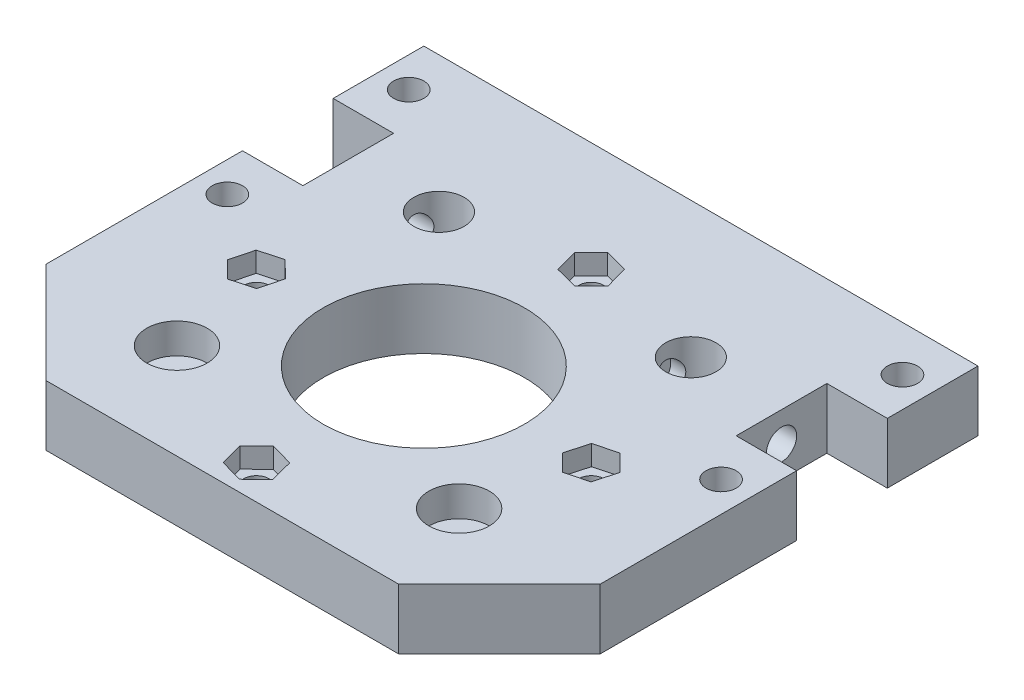
SolidWorks part; units mm, degrees
material "HDPE-green"
ref_plane "Front Plane" through (0, 0, 0) normal (0, 0, 1) x (1, 0, 0)
ref_plane "Top Plane" through (0, 0, 0) normal (0, 1, 0) x (1, 0, 0)
ref_plane "Right Plane" through (0, 0, 0) normal (1, 0, 0) x (0, 0, -1)
sketch "Sketch1" plane through (0, 0, 0) normal (0, 1, 0) x (1, 0, 0)
  line L1 (-33, 25) -> (33, 25)
  line L2 (-33, 25) -> (-33, -70)
  line L3 (-33, -70) -> (33, -70)
  line L4 (33, 25) -> (33, -70)
  circle A0 centre (0, -30) radius 20
  dimension "D6" = 40
  dimension "D1" = 66
  dimension "D2" = 33
  dimension "D3" = 25
  dimension "D4" = 70
  dimension "D5" = 30
extrude "Boss-Extrude1" add sketch "Sketch1" along normal blind 12
sketch "Sketch3" plane through (0, 12, 0) normal (0, 1, 0) x (1, 0, 0)
  line L1 (55, 7) -> (43, 7)
  line L2 (33, 25) -> (33, -70)
  line L3 (43, 7) -> (43, -11)
  line L4 (43, -11) -> (55, -11)
  line L6 (33, -70) -> (55, -70)
  line L7 (55, -70) -> (55, -11)
  line L8 (33, 25) -> (55, 25)
  line L9 (55, 7) -> (55, 25)
  dimension "D1" = 12
  dimension "D2" = 18
  dimension "D3" = 18
  dimension "D4" = 22
extrude "Boss-Extrude3" add sketch "Sketch3" against normal blind 12
mirror "Mirror1" about plane through (0, 0, 0) normal (1, 0, 0) of "Boss-Extrude3"
sketch "Sketch6" plane through (0, 12, 0) normal (0, 1, 0) x (1, 0, 0)
  line L0 (-63.5336, -51) -> (64.8117, -51) construction
  circle A1 centre (-28, -51) radius 6
  circle A2 centre (28, -51) radius 6
  circle A3 centre (0, -30) radius 20 construction
  dimension "D2" = 28
  dimension "D3" = 28
  dimension "D4" = 12
  dimension "D5" = 12
  dimension "D1" = 21
extrude "Cut-Extrude2" cut sketch "Sketch6" against normal blind 6
chamfer "Chamfer1" distance 20 angle 45 2 edges at (55, 6, 70) (-55, 6, 70)
sketch "Sketch7" plane through (0, 12, 0) normal (0, 1, 0) x (1, 0, 0)
  line L0 (-49, 22.071) -> (-49, -31.0852) construction
  line L1 (-59.9918, 16) -> (-35.4854, 16) construction
  line L2 (-63.8876, -20) -> (-39.0752, -20) construction
  line L3 (-55, -11) -> (-43, -11) construction
  line L4 (-42.1899, -2) -> (-20.2042, -2) construction
  line L6 (-43, -11) -> (-43, 7) construction
  circle A0 centre (-49, 16) radius 3
  circle A1 centre (-49, -20) radius 3
  circle A2 centre (-25, -2) radius 5
  dimension "D2" = 6
  dimension "D3" = 6
  dimension "D4" = 18
  dimension "D5" = 10
  dimension "D1" = 9
extrude "Cut-Extrude3" cut sketch "Sketch7" against normal up to next
sketch "Sketch9" plane through (-43, 0, 0) normal (-1, 0, 0) x (0, 0, 1)
  line L0 (11, 12) -> (-7, 12) construction
  line L1 (-7, 0) -> (-7, 12) construction
  circle A0 centre (2, 6) radius 3
  dimension "D1" = 6
  dimension "D2" = 6
  dimension "D3" = 9
extrude "Cut-Extrude5" cut sketch "Sketch9" against normal blind 25
mirror "Mirror2" about plane through (0, 0, 0) normal (1, 0, 0) of "Cut-Extrude5", "Cut-Extrude3"
sketch "Sketch10" plane through (0, 0, 0) normal (0, -1, 0) x (1, 0, 0)
  circle A0 centre (0, 63.234) radius 2.5 construction
  circle A1 centre (-33.234, 30) radius 2.5 construction
  circle A2 centre (0, -3.234) radius 2.5 construction
  circle A3 centre (33.234, 30) radius 2.5 construction
  circle A4 centre (0, 63.234) radius 2.5
  circle A5 centre (-33.234, 30) radius 2.5
  circle A6 centre (0, -3.234) radius 2.5
  circle A7 centre (33.234, 30) radius 2.5
extrude "Cut-Extrude6" cut sketch "Sketch10" against normal up to next
sketch "Sketch12" plane through (0, 12, 0) normal (0, 1, 0) x (1, 0, 0)
  line L1 (3.3343, -59.9549) -> (-1.1727, -58.7069)
  line L2 (-1.1727, -58.7069) -> (-4.5069, -61.986)
  line L3 (-4.5069, -61.986) -> (-3.3343, -66.5132)
  line L4 (-3.3343, -66.5132) -> (1.1727, -67.7611)
  line L5 (1.1727, -67.7611) -> (4.5069, -64.482)
  line L6 (4.5069, -64.482) -> (3.3343, -59.9549)
  line L7 (-29.8998, -33.2791) -> (-28.7271, -28.752)
  line L8 (-28.7271, -28.752) -> (-32.0613, -25.4729)
  line L9 (-32.0613, -25.4729) -> (-36.5683, -26.7209)
  line L10 (-36.5683, -26.7209) -> (-37.741, -31.248)
  line L11 (-37.741, -31.248) -> (-34.4067, -34.5271)
  line L12 (-34.4067, -34.5271) -> (-29.8998, -33.2791)
  line L13 (-3.2828, -0.0967) -> (1.2431, -1.2743)
  line L14 (1.2431, -1.2743) -> (4.5258, 2.0564)
  line L15 (4.5258, 2.0564) -> (3.2828, 6.5647)
  line L16 (3.2828, 6.5647) -> (-1.2431, 7.7423)
  line L17 (-1.2431, 7.7423) -> (-4.5258, 4.4116)
  line L18 (-4.5258, 4.4116) -> (-3.2828, -0.0967)
  line L19 (29.9513, -26.6693) -> (28.7082, -31.1776)
  line L20 (28.7082, -31.1776) -> (31.9909, -34.5083)
  line L21 (31.9909, -34.5083) -> (36.5168, -33.3307)
  line L22 (36.5168, -33.3307) -> (37.7599, -28.8224)
  line L23 (37.7599, -28.8224) -> (34.4771, -25.4917)
  line L24 (34.4771, -25.4917) -> (29.9513, -26.6693)
  circle A0 centre (0, -63.234) radius 4.05 construction
  circle A1 centre (-33.234, -30) radius 4.05 construction
  circle A2 centre (0, 3.234) radius 4.05 construction
  circle A3 centre (33.234, -30) radius 4.05 construction
  dimension "D1" = 8.1
  dimension "D2" = 8.1
  dimension "D3" = 8.1
  dimension "D4" = 8.1
extrude "Cut-Extrude7" cut sketch "Sketch12" against normal blind 4
